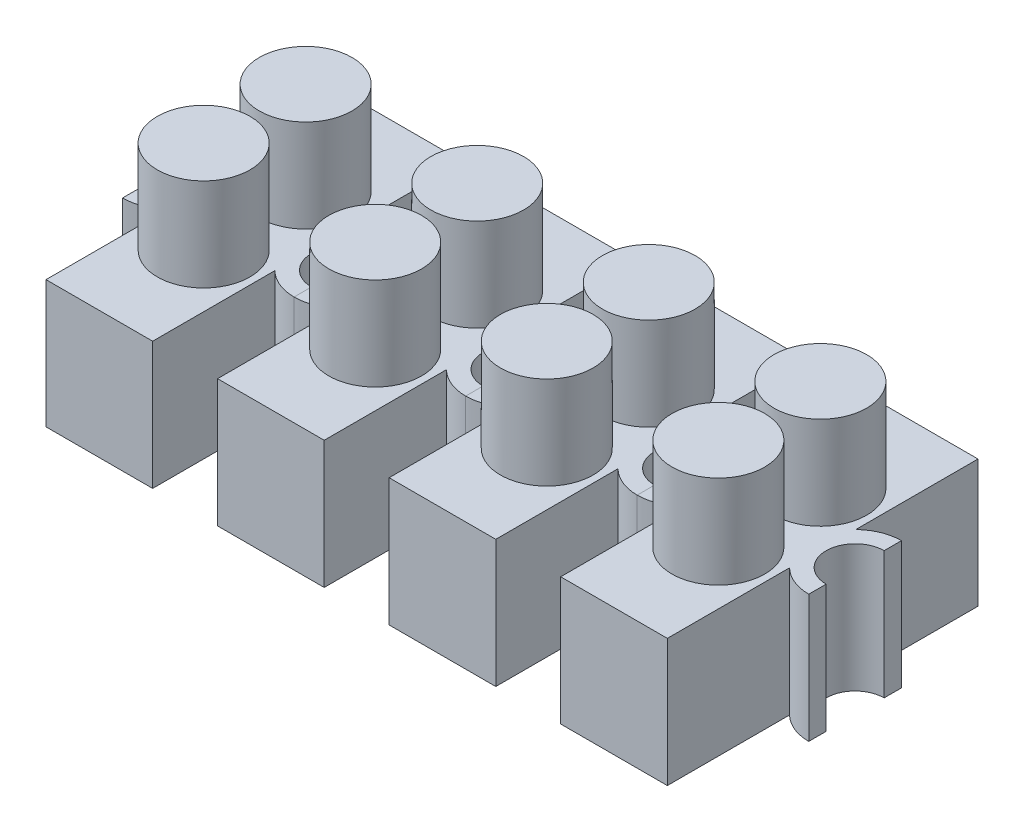
SolidWorks part; units mm, degrees
ref_plane "Front Plane" through (0, 0, 0) normal (0, 0, 1) x (1, 0, 0)
ref_plane "Top Plane" through (0, 0, 0) normal (0, 1, 0) x (1, 0, 0)
ref_plane "Right Plane" through (0, 0, 0) normal (1, 0, 0) x (0, 0, -1)
sketch "Sketch2" plane through (0, 0, 0) normal (0, 1, 0) x (1, 0, 0)
  line L0 (2.921, 8.509) -> (-2.921, 8.509)
  line L1 (-2.921, 8.509) -> (-2.921, 1.8139)
  line L2 (0, -9.3599) -> (0, 9.3599) construction
  line L3 (2.921, 8.509) -> (2.921, 1.8139)
  line L4 (-5.1689, 0) -> (5.1689, 0) construction
  line L5 (-2.921, -8.509) -> (-2.921, -1.8139)
  line L6 (2.921, -8.509) -> (2.921, -1.8139)
  line L7 (2.921, -8.509) -> (-2.921, -8.509)
  line L8 (-4.699, 2.54) -> (-4.699, -2.54) construction
  line L9 (4.699, 2.54) -> (4.699, -2.54) construction
  line L10 (-4.699, 1.5875) -> (-4.699, 2.54)
  line L11 (-4.699, -2.54) -> (-4.699, -1.5875)
  line L12 (4.699, -2.54) -> (4.699, -1.5875)
  line L13 (4.699, 1.5875) -> (4.699, 2.54)
  arc A0 (-4.699, -2.54) -> (-2.921, -1.8139) centre (-4.699, 0) ccw
  arc A1 (-4.699, 2.54) -> (-2.921, 1.8139) centre (-4.699, 0) cw
  arc A2 (4.699, -2.54) -> (2.921, -1.8139) centre (4.699, 0) cw
  arc A3 (4.699, 2.54) -> (2.921, 1.8139) centre (4.699, 0) ccw
  arc A4 (-4.699, 1.5875) -> (-4.699, -1.5875) centre (-4.699, 0) cw
  arc A5 (4.699, 1.5875) -> (4.699, -1.5875) centre (4.699, 0) ccw
  point P7 (0, 8.509)
  point P17 (-4.699, 0)
  point P18 (4.699, 0)
  dimension "D1" = 1.5875
  dimension "D2" = 5.842
  dimension "D3" = 1.778
  dimension "D4" = 5.08
  dimension "D5" = 17.018
extrude "Boss-Extrude1" add sketch "Sketch2" along normal blind 6.985 contours L3 A3 L13 A5 L12 A2 L6 L7 L5 A0 L11 A4 L10 A1 L1 L0
sketch "Sketch3" plane through (0, 0, 0) normal (0, -1, 0) x (1, 0, 0)
  line L1 (-2.286, 7.747) -> (2.286, 7.747)
  line L2 (-2.286, 7.747) -> (-2.286, -7.747)
  line L3 (-2.286, -7.747) -> (2.286, -7.747)
  line L4 (2.286, 7.747) -> (2.286, -7.747)
  line L5 (0, -7.747) -> (0, 7.747) construction
  point P4 (0, 7.747)
  point P6 (2.286, 0)
  point P7 (-2.286, 0)
  point P8 (0, -7.747)
  point P9 (0, 0)
  dimension "D1" = 4.572
  dimension "D2" = 15.494
extrude "Cut-Extrude1" cut sketch "Sketch3" against normal blind 1.27
sketch "Sketch6" plane through (0, 6.985, 0) normal (0, 1, 0) x (1, 0, 0)
  line L0 (0, -3.8418) -> (0, 3.8418) construction
  line L1 (0, 2.794) -> (0, -2.794) construction
  line L2 (-3.8418, 0) -> (3.8418, 0) construction
  line L3 (0, -5.334) -> (0, 5.334) construction
  circle A0 centre (0, 2.794) radius 2.54
  circle A1 centre (0, -2.794) radius 2.54
  point P6 (0, 0)
  dimension "D1" = 5.08
  dimension "D2" = 10.668
extrude "Boss-Extrude3" add sketch "Sketch6" along normal blind 5.08
pattern_linear "LPattern1" count 4 spacing 9.398 along (-1, 0, 0) of bodies 104
equation "\"Terminals\"= 4"
